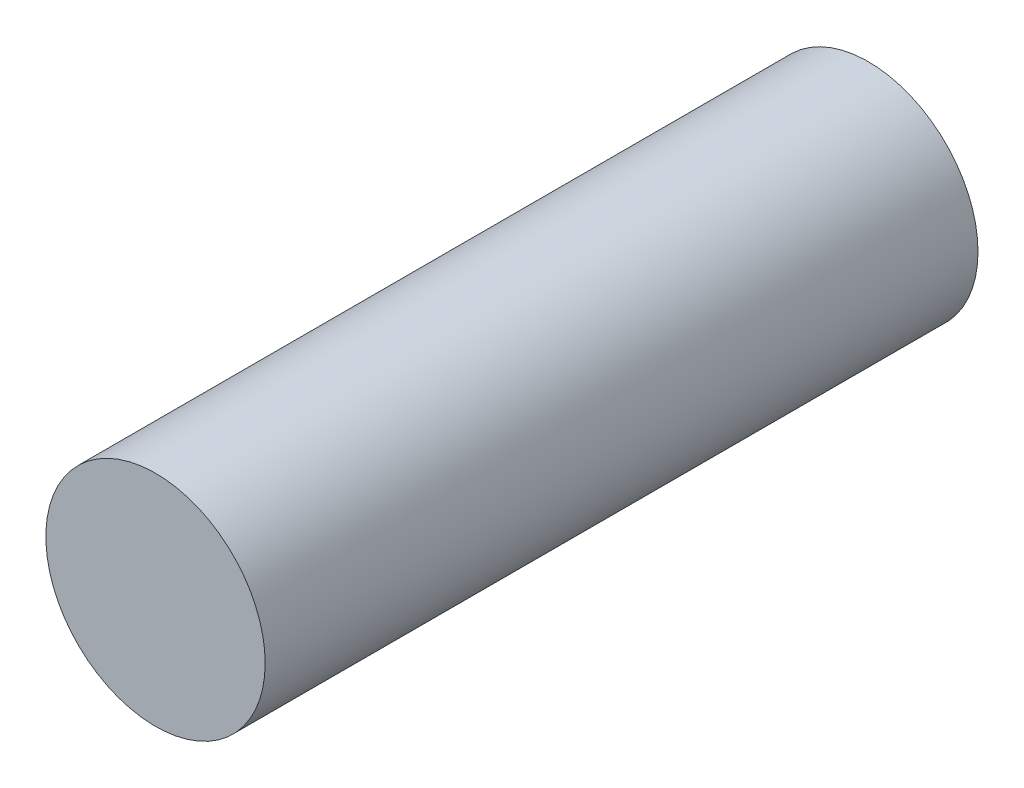
SolidWorks part; units mm, degrees
material "ﾎﾟﾘｴﾁﾚﾝ(PE)低/中密度"
ref_plane "正面" through (0, 0, 0) normal (0, 0, 1) x (1, 0, 0)
ref_plane "平面" through (0, 0, 0) normal (0, 1, 0) x (1, 0, 0)
ref_plane "右側面" through (0, 0, 0) normal (1, 0, 0) x (0, 0, -1)
sketch "ｽｹｯﾁ1" plane through (0, 0, 0) normal (0, 0, 1) x (1, 0, 0)
  circle A0 centre (0, 0) radius 10
  dimension "D1" = 20
extrude "ﾎﾞｽ - 押し出し1" add sketch "ｽｹｯﾁ1" along normal blind 65
